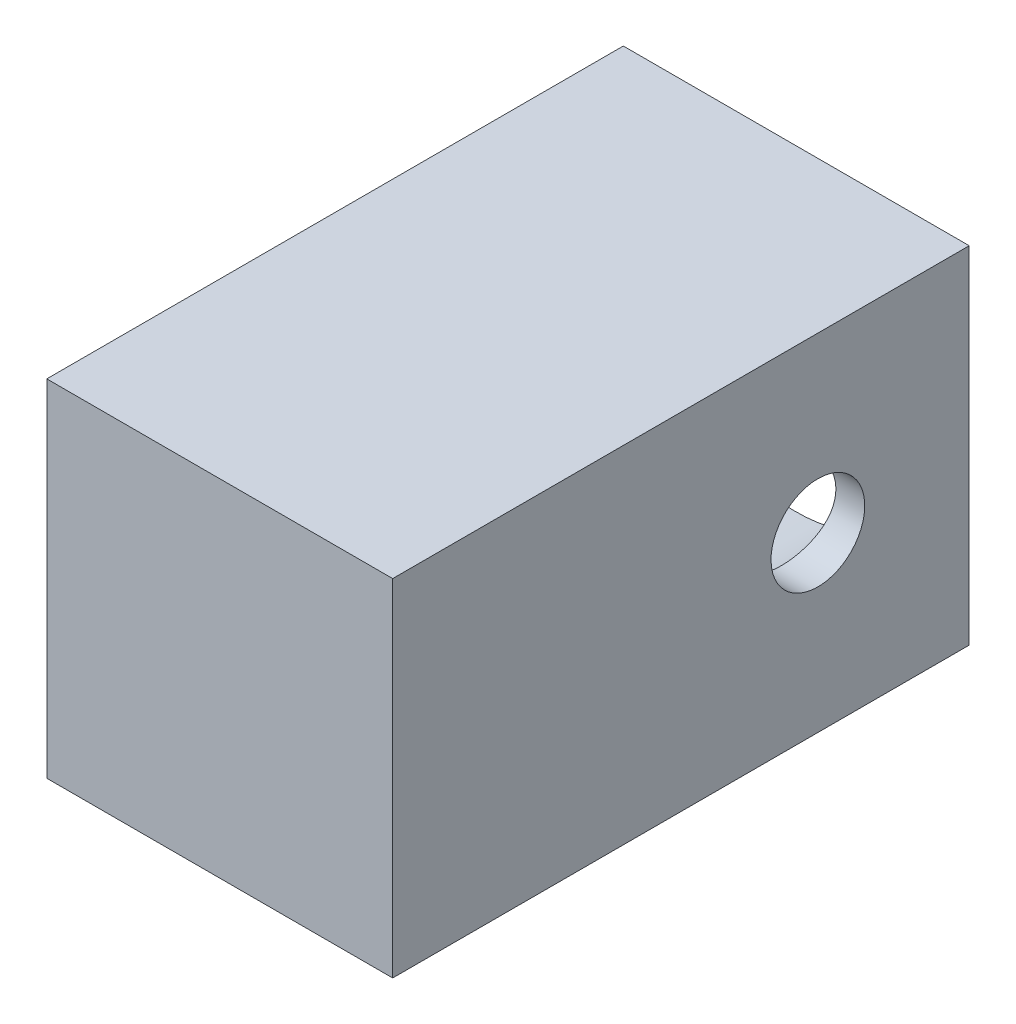
SolidWorks part; units mm, degrees
ref_plane "前视基准面" through (0, 0, 0) normal (0, 0, 1) x (1, 0, 0)
ref_plane "上视基准面" through (0, 0, 0) normal (0, 1, 0) x (1, 0, 0)
ref_plane "右视基准面" through (0, 0, 0) normal (1, 0, 0) x (0, 0, -1)
sketch "草图3" plane through (0, 0, 26.489) normal (0, 0, 1) x (1, 0, 0)
  line L1 (-12, 12) -> (12, 12)
  line L2 (-12, 12) -> (-12, -12)
  line L3 (-12, -12) -> (12, -12)
  line L4 (12, 12) -> (12, -12)
  line L5 (-12, 12) -> (12, -12) construction
  line L6 (-12, -12) -> (12, 12) construction
  point P0 (0, 0)
  dimension "D1" = 24
  dimension "D2" = 24
extrude "凸台-拉伸1" add sketch "草图3" against normal blind 20
sketch "草图4" plane through (0, 0, 6.489) normal (0, 0, -1) x (-1, 0, 0)
  circle A0 centre (0, 0) radius 10
extrude "切除-拉伸1" cut sketch "草图4" against normal up to next
sketch "草图6" plane through (0, 0, 26.489) normal (0, 0, 1) x (1, 0, 0)
  line L1 (-12, 12) -> (12, 12)
  line L2 (-12, 12) -> (-12, -12)
  line L3 (-12, -12) -> (12, -12)
  line L4 (12, 12) -> (12, -12)
  line L5 (-12, 12) -> (12, -12) construction
  line L6 (-12, -12) -> (12, 12) construction
  point P0 (0, 0)
extrude "凸台-拉伸2" add sketch "草图6" along normal blind 20
sketch "草图8" plane through (12, 0, 0) normal (1, 0, 0) x (0, 0, -1)
  circle A0 centre (-16.989, 0) radius 3.25
extrude "切除-拉伸2" cut sketch "草图8" against normal through all
